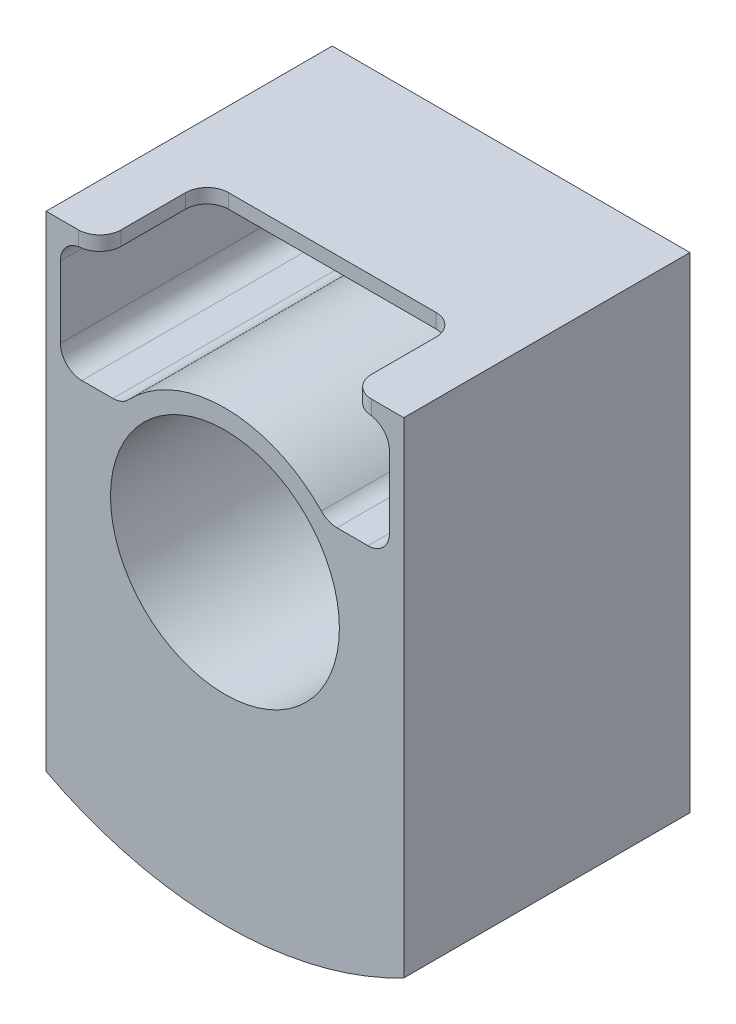
SolidWorks part; units mm, degrees
ref_plane "Front Plane" through (0, 0, 0) normal (0, 0, 1) x (1, 0, 0)
ref_plane "Top Plane" through (0, 0, 0) normal (0, 1, 0) x (1, 0, 0)
ref_plane "Right Plane" through (0, 0, 0) normal (1, 0, 0) x (0, 0, -1)
sketch "Sketch1" plane through (0, 0, 0) normal (0, 0, 1) x (1, 0, 0)
  line L1 (0, 0) -> (0, -53.975) construction
  line L2 (-25, 0) -> (-25, -47.8362)
  line L3 (25, 0) -> (25, -47.8362)
  line L4 (-25, 0) -> (-25, 20)
  line L5 (-25, 20) -> (25, 20)
  line L6 (25, 20) -> (25, 0)
  arc A0 (-25, -47.8362) -> (25, -47.8362) centre (0, 0) ccw
  dimension "D1" = 107.95
  dimension "D2" = 50
  dimension "D3" = 20
extrude "Boss-Extrude2" add sketch "Sketch1" along normal blind 40
sketch "Sketch2" plane through (0, 0, 40) normal (0, 0, 1) x (1, 0, 0)
  line L6 (0, 6) -> (0, -26) construction
  circle A0 centre (0, -10) radius 16
  dimension "D2" = 32
  dimension "D1" = 10
extrude "Cut-Extrude1" cut sketch "Sketch2" against normal through all both
sketch "Sketch4" plane through (0, 0, 40) normal (0, 0, 1) x (1, 0, 0)
  line L0 (-23, 18) -> (23, 18)
  line L3 (0, 20) -> (0, 6) construction
  line L4 (25, 20) -> (-25, 20) construction
  line L5 (23, 2) -> (14.3178, 2)
  line L6 (-23, 18) -> (-23, 2)
  line L7 (-23, 2) -> (-14.3178, 2)
  line L8 (-25, 20) -> (-25, -47.8362) construction
  line L9 (23, 18) -> (23, 2)
  circle A2 centre (0, -10) radius 16 construction
  arc A3 (14.3178, 2) -> (-14.3178, 2) centre (0, -10) ccw
  point P2 (0, 13)
  point P14 (0, 18)
  dimension "D1" = 37.3631
  dimension "D2" = 2
  dimension "D3" = 2
  dimension "D4" = 16
extrude "Cut-Extrude3" cut sketch "Sketch4" against normal through all
fillet "Fillet1" radius 3 6 edges at (23, 18, 20) (23, 2, 20) (14.3178, 2, 20) (-14.3178, 2, 20) (-23, 2, 20) (-23, 18, 20)
sketch "Sketch5" plane through (0, 20, 0) normal (0, 1, 0) x (1, 0, 0)
  line L0 (25, -40) -> (-25, -40) construction
  line L1 (-17.5, -40) -> (17.5, -40)
  line L2 (-17.5, -40) -> (-17.5, -25)
  line L3 (-17.5, -25) -> (17.5, -25)
  line L4 (17.5, -40) -> (17.5, -25)
  line L5 (0, 0) -> (0, -40) construction
  dimension "D1" = 35
  dimension "D2" = 15
extrude "Cut-Extrude4" cut sketch "Sketch5" against normal blind 10
fillet "Fillet2" radius 3 4 edges at (17.5, 19, 40) (17.5, 19, 25) (-17.5, 19, 25) (-17.5, 19, 40)
